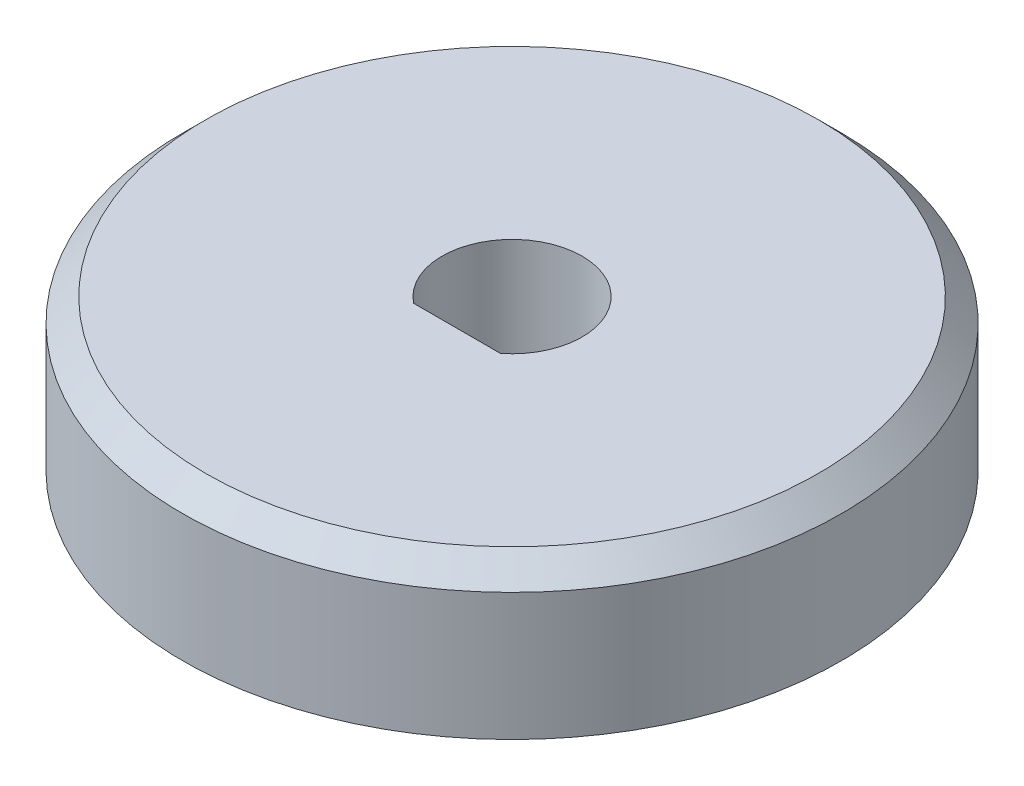
SolidWorks part; units mm, degrees
ref_plane "Front Plane" through (0, 0, 0) normal (0, 0, 1) x (1, 0, 0)
ref_plane "Top Plane" through (0, 0, 0) normal (0, 1, 0) x (1, 0, 0)
ref_plane "Right Plane" through (0, 0, 0) normal (1, 0, 0) x (0, 0, -1)
sketch "Sketch1" plane through (0, 0, 0) normal (0, 1, 0) x (1, 0, 0)
  line L0 (-1.8735, -2.375) -> (1.8735, -2.375)
  line L1 (0, -2.375) -> (0, 3.025) construction
  circle A0 centre (0, 0) radius 14.225
  arc A1 (1.8735, -2.375) -> (-1.8735, -2.375) centre (0, 0) ccw
  dimension "D1" = 28.45
  dimension "D2" = 6.05
  dimension "D3" = 5.4
extrude "Boss-Extrude1" add sketch "Sketch1" along normal blind 6.5
chamfer "Chamfer1" distance 1 angle 45 1 edges at (0, 6.5, 14.225)
